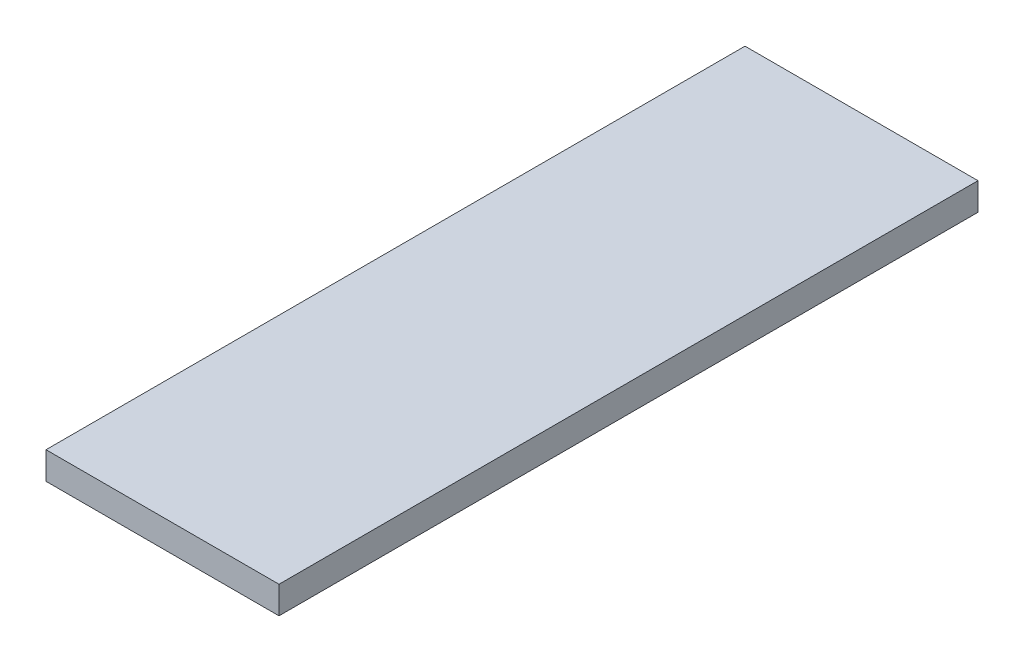
SolidWorks part; units mm, degrees
ref_plane "Front Plane" through (0, 0, 0) normal (0, 0, 1) x (1, 0, 0)
ref_plane "Top Plane" through (0, 0, 0) normal (0, 1, 0) x (1, 0, 0)
ref_plane "Right Plane" through (0, 0, 0) normal (1, 0, 0) x (0, 0, -1)
sketch "Sketch1" plane through (0, 0, 0) normal (0, 0, 1) x (1, 0, 0)
  line L1 (0, 0) -> (101.6, 0)
  line L2 (0, 0) -> (0, 11.938)
  line L3 (0, 11.938) -> (101.6, 11.938)
  line L4 (101.6, 0) -> (101.6, 11.938)
  dimension "D1" = 11.938
  dimension "D2" = 101.6
extrude "base" add sketch "Sketch1" along normal blind 304.8
equation "\"baseplate_thickness\"=0.47"
equation "\"D1@Sketch1\"=\"baseplate_thickness\""
equation "\"baseplate_length\"= 12"
equation "\"D1@base\" = \"baseplate_length\""
equation "\"baseplate_width\"= 4"
equation "\"D2@Sketch1\"=\"baseplate_width\""
equation "\"slider_width\"= 2"
equation "\"slider_length\"= 4"
equation "\"slider_thickness\"= 1"
equation "\"side_radial_clearance\"= 0.01"
equation "\"front_radial_clearance\"= 0.01"
equation "\"side_plate_width\"= (\"baseplate_width\" - \"slider_width\" - ( 2 * \"side_radial_clearance\" ))/2"
equation "\"side_plate_height\"= \"slider_thickness\" + ( 2 * \"front_radial_clearance\" )"
equation "\"keeper_plate_thickness\"= 0.5"
equation "\"rail_width\"= 1"
equation "\"rail_radial_clearance\"= 0.25"
